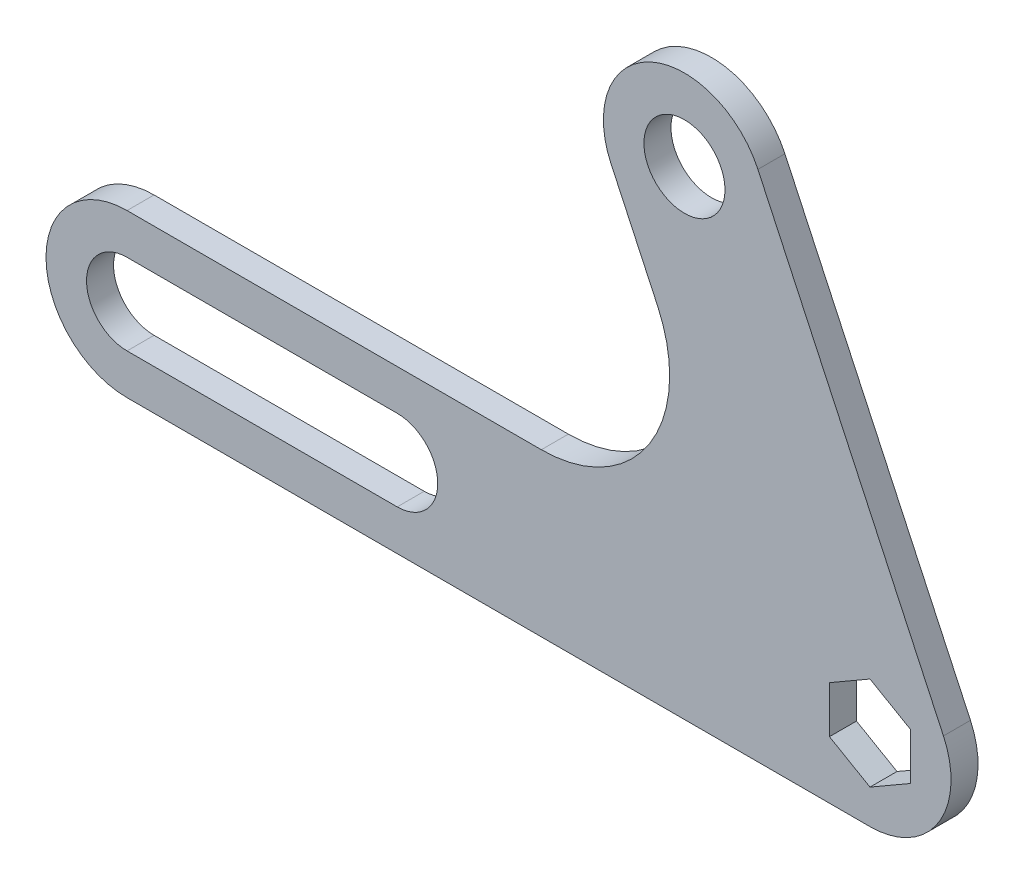
SolidWorks part; units mm, degrees
ref_plane "Front Plane" through (0, 0, 0) normal (0, 0, 1) x (1, 0, 0)
ref_plane "Top Plane" through (0, 0, 0) normal (0, 1, 0) x (1, 0, 0)
ref_plane "Right Plane" through (0, 0, 0) normal (1, 0, 0) x (0, 0, -1)
sketch "Sketch1" plane through (0, 0, 0) normal (0, 0, 1) x (1, 0, 0)
  line L0 (0, 0) -> (110, 0)
  line L1 (120.8757, 17.0714) -> (93.4055, 75.9814)
  line L2 (71.6541, 65.8386) -> (78.5596, 51.0297)
  line L3 (61.3397, 24) -> (0, 24)
  line L4 (0, 12) -> (40, 12) construction
  line L5 (0, 18) -> (40, 18)
  line L6 (0, 6) -> (40, 6)
  line L7 (40, 12) -> (110, 12) construction
  line L14 (110, 12) -> (82.5298, 70.91) construction
  line L15 (71.6541, 65.8386) -> (93.4055, 75.9814) construction
  line L16 (110, 18.9282) -> (104, 15.4641)
  line L17 (104, 15.4641) -> (104, 8.5359)
  line L18 (104, 8.5359) -> (110, 5.0718)
  line L19 (110, 5.0718) -> (116, 8.5359)
  line L20 (116, 8.5359) -> (116, 15.4641)
  line L21 (116, 15.4641) -> (110, 18.9282)
  arc A1 (93.4055, 75.9814) -> (71.6541, 65.8386) centre (82.5298, 70.91) ccw
  arc A2 (78.5596, 51.0297) -> (61.3397, 24) centre (61.3397, 43) cw
  arc A3 (0, 24) -> (0, 0) centre (0, 12) ccw
  arc A4 (0, 18) -> (0, 6) centre (0, 12) ccw
  arc A5 (40, 6) -> (40, 18) centre (40, 12) ccw
  circle A6 centre (110, 12) radius 6 construction
  circle A7 centre (82.5298, 70.91) radius 6
  arc A8 (110, 0) -> (120.8757, 17.0714) centre (110, 12) ccw
  point P13 (20, 12)
  dimension "D3" = 12
  dimension "D5" = 12
  dimension "D6" = 19
  dimension "D7" = 12
  dimension "D10" = 6
  dimension "D12" = 12
  dimension "D2" = 40
  dimension "D4" = 65
  dimension "D8" = 12
  dimension "D9" = 110
  dimension "D11" = 65
extrude "Boss-Extrude1" add sketch "Sketch1" along normal blind 4
